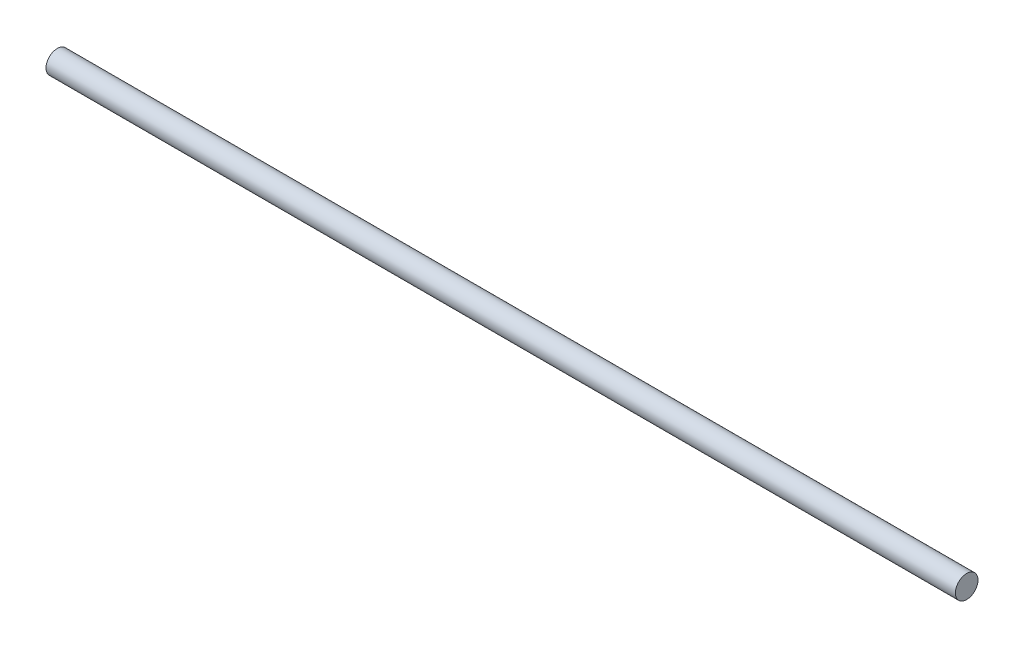
SolidWorks part; units mm, degrees
ref_plane "Front Plane" through (0, 0, 0) normal (0, 0, 1) x (1, 0, 0)
ref_plane "Top Plane" through (0, 0, 0) normal (0, 1, 0) x (1, 0, 0)
ref_plane "Right Plane" through (0, 0, 0) normal (1, 0, 0) x (0, 0, -1)
sketch "Sketch1" plane through (0, 0, 0) normal (1, 0, 0) x (0, 0, -1)
  circle A0 centre (0, 0) radius 4.445
  dimension "D1" = 8.89
extrude "Boss-Extrude1" add sketch "Sketch1" along normal blind 357.378
sketch "Sketch3" plane through (0, 0, 0) normal (-1, 0, 0) x (0, 0, 1)
  point P0 (4.445, 0)
